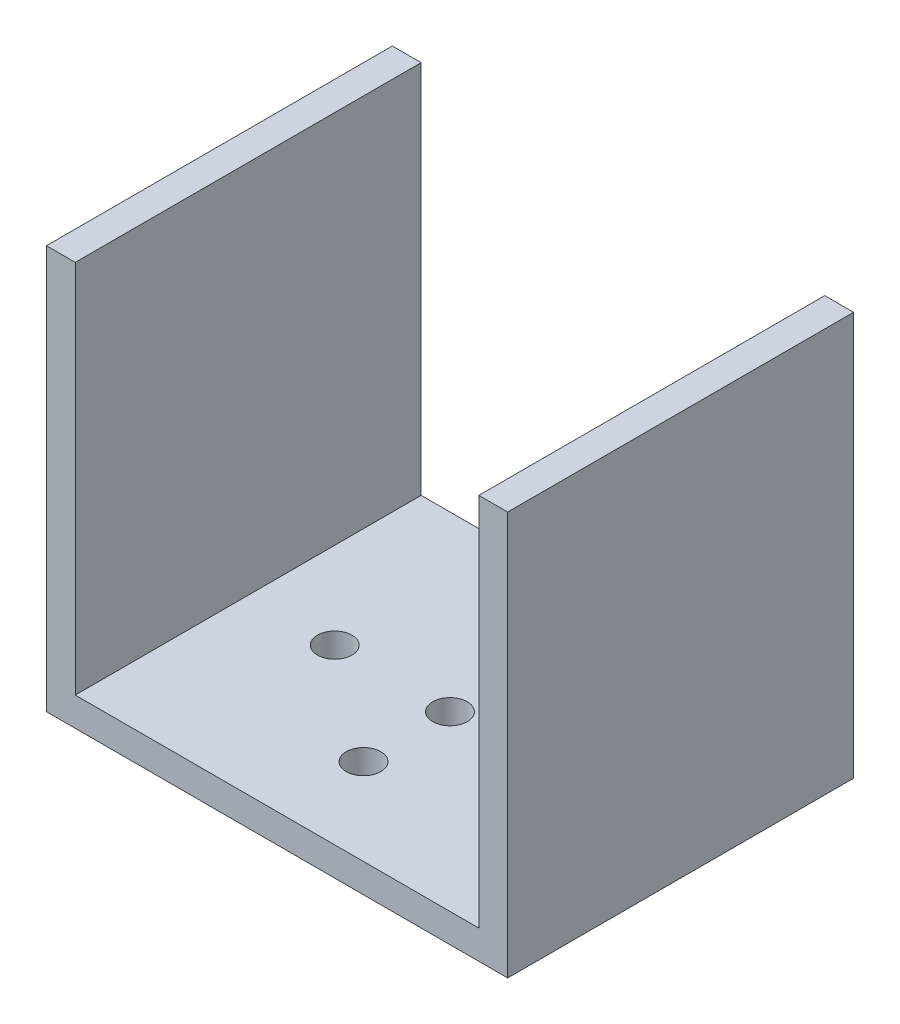
SolidWorks part; units mm, degrees
ref_plane "Front Plane" through (0, 0, 0) normal (0, 0, 1) x (1, 0, 0)
ref_plane "Top Plane" through (0, 0, 0) normal (0, 1, 0) x (1, 0, 0)
ref_plane "Right Plane" through (0, 0, 0) normal (1, 0, 0) x (0, 0, -1)
sketch "Sketch1" plane through (0, 0, 0) normal (0, 0, 1) x (1, 0, 0)
  line L0 (0, 0) -> (80, 0)
  line L1 (80, 0) -> (80, 70)
  line L2 (80, 70) -> (0, 70)
  line L3 (0, 70) -> (0, 0)
  line L4 (5, 70) -> (75, 70)
  line L5 (75, 70) -> (75, 5)
  line L6 (75, 5) -> (5, 5)
  line L7 (5, 5) -> (5, 70)
  dimension "D1" = 80
  dimension "D2" = 70
  dimension "D3" = 70
  dimension "D4" = 5
  dimension "D5" = 65
extrude "Boss-Extrude1" add sketch "Sketch1" against normal blind 60 contours L6 L7 L2 L3 L0 L1 L5
sketch "Sketch2" plane through (0, 5, 0) normal (0, 1, 0) x (1, 0, 0)
  line L0 (5, 30) -> (20, 30) construction
  line L1 (5, 60) -> (5, 0) construction
  line L2 (40, -4.0723) -> (40, 64.3573) construction
  line L3 (-10.4698, 30) -> (87.5962, 30) construction
  line L4 (75, 60) -> (5, 60) construction
  line L5 (75, 60) -> (75, 0) construction
  circle A0 centre (40, 30) radius 3
  circle A1 centre (20, 30) radius 3
  circle A2 centre (40, 45) radius 3
  circle A3 centre (40, 15) radius 3
  circle A4 centre (60, 30) radius 3
  point P15 (0, 0)
  dimension "D1" = 6
  dimension "D3" = 6
  dimension "D4" = 6
  dimension "D2" = 15
  dimension "D5" = 15
  dimension "D6" = 15
extrude "Cut-Extrude1" cut sketch "Sketch2" against normal through all
